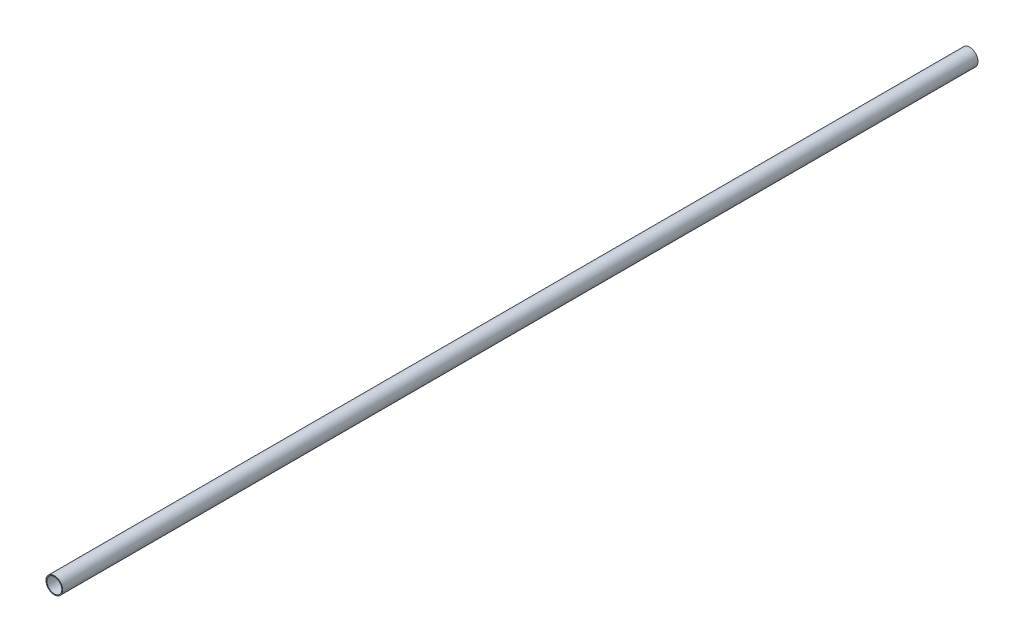
SolidWorks part; units mm, degrees
material "AISI 304"
ref_plane "Front" through (0, 0, 0) normal (0, 0, 1) x (1, 0, 0)
ref_plane "Top" through (0, 0, 0) normal (0, 1, 0) x (1, 0, 0)
ref_plane "Right" through (0, 0, 0) normal (1, 0, 0) x (0, 0, -1)
sketch "Sketch1" plane through (0, 0, 0) normal (0, 0, 1) x (1, 0, 0)
  line L0 (0, 11.4554) -> (0, 12.7) construction
  circle A0 centre (0, 0) radius 12.7
  circle A1 centre (0, 0) radius 11.4554
  dimension "D1" = 25.4
  dimension "D3" = 22.9108
  dimension "D2" = 1.2446
extrude "Boss-Extrude1" add sketch "Sketch1" along normal blind 1397
